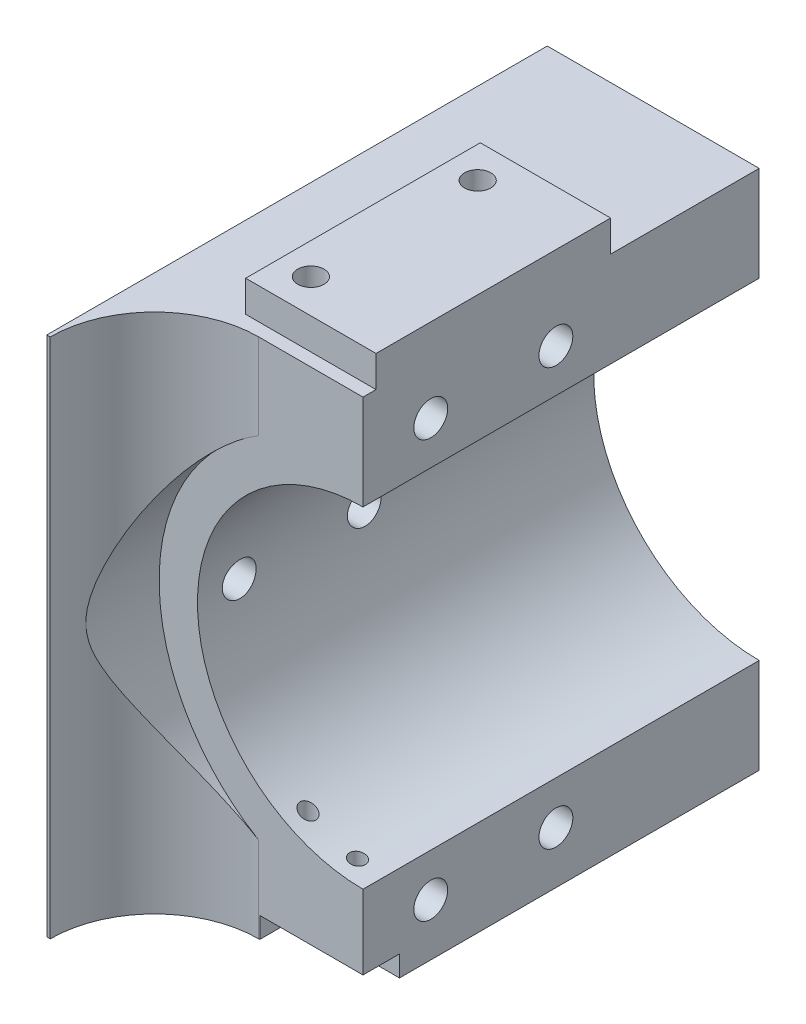
SolidWorks part; units mm, degrees
other "Markup1"
sketch "Sketch12" plane through (-50, 56, -10) normal (-0.1438, 0.9756, -0.1662) x (-0.9889, -0.1353, 0.0611)
material "6061-T6 (SS)"
ref_plane "Front Plane" through (0, 0, 0) normal (0, 0, 1) x (1, 0, 0)
ref_plane "Top Plane" through (0, 0, 0) normal (0, 1, 0) x (1, 0, 0)
ref_plane "Right Plane" through (0, 0, 0) normal (1, 0, 0) x (0, 0, -1)
sketch "Sketch1" plane through (0, 0, 0) normal (0, 0, 1) x (1, 0, 0)
  circle A2 centre (0, 0) radius 31.75
  circle A4 centre (0, 0) radius 39.1
  circle A5 centre (0, 0) radius 38.1 construction
  dimension "D1" = 1
  dimension "D2" = 63.5
extrude "Centre Hole for L2" add sketch "Sketch1" along normal blind 40 and the other way blind 10 contours A4 | A2
sketch "Sketch2" plane through (0, 0, 40) normal (0, 0, 1) x (1, 0, 0)
  line L0 (0, 48.4974) -> (0, 0) construction
  line L5 (-50, 50) -> (-50, -50)
  line L12 (0, 0) -> (72.986, 0) construction
  line L16 (-50, 50) -> (50, 50)
  line L17 (50, 50) -> (50, -50)
  line L18 (-50, -50) -> (50, -50)
  circle A2 centre (0, 0) radius 39.1
  circle A3 centre (0, 0) radius 39.1 construction
  point P13 (0, 50)
  dimension "D1" = 50
  dimension "D2" = 100
extrude "Main Structure" add sketch "Sketch2" along normal blind 60 and the other way blind 50 contours L5 L18 L17 L16 A2
sketch "Sketch3" plane through (-50, 0, 0) normal (-1, 0, 0) x (0, 0, 1)
  line L0 (100, 50) -> (100, -50) construction
  line L1 (100, 50) -> (100, -50)
  line L2 (-10, 50) -> (100, 50) construction
  line L3 (-10, -50) -> (100, -50) construction
  line L4 (-10, 50) -> (100, 50) construction
  arc A0 (100, 50) -> (100, -50) centre (100, 0) cw
extrude "Bearing Curve" add sketch "Sketch3" against normal blind 10 contours A0 L1
mirror "Upright Mirror" about plane through (0, 0, 0) normal (1, 0, 0) of "Bearing Curve"
sketch "Sketch6" plane through (-50, 0, 0) normal (-1, 0, 0) x (0, 0, 1)
  circle A0 centre (100, 0) radius 10.5
  dimension "D1" = 21
extrude "Shaft Hole" cut sketch "Sketch6" against normal up to surface (10 mm away) up to face at (-40, 0, 125)
sketch "Sketch4" plane through (0, 50, 0) normal (0, 1, 0) x (1, 0, 0)
  line L0 (0, -100) -> (0, 10) construction
  line L3 (-40, -100) -> (-40, -60)
  line L6 (40, -100) -> (40, -60)
  line L7 (-50, 10) -> (50, 10) construction
  line L8 (-40, -100) -> (40, -100) construction
  line L9 (-20, -40) -> (20, -40)
  line L10 (-40, -100) -> (40, -100)
  arc A0 (-40, -60) -> (-20, -40) centre (-20, -60) cw
  arc A1 (40, -60) -> (20, -40) centre (20, -60) ccw
  point P17 (0, -100)
  dimension "D2" = 20
  dimension "D1" = 50
extrude "Wrist Cutout" cut sketch "Sketch4" against normal through all
ref_plane "Plane1" through (0, 0, 0) normal (-1, 0, 0) x (0, 0, 1)
other "SurfaceCut1"
sketch "Sketch11" plane through (0, 50, 0) normal (0, 1, 0) x (1, 0, 0)
  line L0 (0, -40) -> (0, 10) construction
  line L1 (0, -37.5) -> (-25, -37.5)
  line L2 (0, -37.5) -> (0, 7.5)
  line L3 (0, 7.5) -> (-25, 7.5)
  line L4 (-25, -37.5) -> (-25, 7.5)
  line L5 (-50, 10) -> (0, 10) construction
  circle A0 centre (-19, 1) radius 2.525
  circle A1 centre (-19, -31) radius 2.525
  dimension "D4" = 5.05
  dimension "D5" = 19
  dimension "D6" = 6.5
  dimension "D7" = 5.05
  dimension "D8" = 19
  dimension "D1" = 45
  dimension "D2" = 25
  dimension "D3" = 2.5
  dimension "6.5" = 6.5
extrude "Boss-Extrude1" add sketch "Sketch11" along normal blind 6
sketch "Sketch15" plane through (0, -50, 0) normal (0, -1, 0) x (-1, 0, 0)
  line L1 (0, -40) -> (19.8, -40)
  line L2 (0, -40) -> (0, -33)
  line L3 (0, -33) -> (19.8, -33)
  line L4 (19.8, -40) -> (19.8, -33)
  dimension "D1" = 19.8
  dimension "D2" = 7
extrude "Cut-Extrude4" cut sketch "Sketch15" against normal blind 4
sketch "Sketch16" plane through (0, -46, 0) normal (0, -1, 0) x (-1, 0, 0)
  line L0 (19.8, -40) -> (19.8, -33) construction
  line L1 (19.8, -33) -> (0, -33) construction
  line L2 (14.65, -35.9) -> (4.8172, -35.9) construction
  circle A0 centre (14.65, -35.9) radius 1.5
  circle A1 centre (5.15, -35.9) radius 1.5
  point P4 (19.8, -36.5)
  dimension "D1" = 3
  dimension "D2" = 5.15
  dimension "D3" = 2.9
  dimension "D4" = 3
  dimension "D5" = 9.5
extrude "Cut-Extrude5" cut sketch "Sketch16" against normal up to surface (17.8319 mm away)
sketch "Sketch18" plane through (-50, 0, 0) normal (-1, 0, 0) x (0, 0, 1)
  line L2 (-10, 50) -> (-10, -50) construction
  line L4 (-10, 50) -> (100, 50) construction
  circle A0 centre (8, 0) radius 3.25
  circle A1 centre (32, 0) radius 3.25
  dimension "D1" = 6.5
  dimension "D2" = 6.5
  dimension "D3" = 18
  dimension "D4" = 50
  dimension "D6" = 24
extrude "Cut-Extrude6" cut sketch "Sketch18" against normal through all and the other way through all
sketch "Sketch19" plane through (-40, 0, 0) normal (1, 0, 0) x (0, 0, -1)
  line L3 (-60, 50) -> (-100, 50)
  line L4 (-100, -50) -> (-60, -50)
  line L5 (-60, -50) -> (-60, 50)
  line L6 (-60, 50) -> (-100, 50)
  line L7 (-100, -50) -> (-60, -50)
  line L8 (-60, -50) -> (-60, 50)
  arc A1 (-100, 50) -> (-100, -50) centre (-100, 0) ccw
  arc A2 (-100, 50) -> (-100, -50) centre (-100, 0) ccw
  dimension "D1" = 0
extrude "Cut-Extrude7" cut sketch "Sketch19" against normal blind 1.5875
sketch "Sketch9" plane through (-41.5875, 0, 0) normal (1, 0, 0) x (0, 0, -1)
  circle A0 centre (-100, 0) radius 12.05
  dimension "D1" = 24.1
extrude "Bearing" cut sketch "Sketch9" against normal blind 5
sketch "Sketch20" plane through (-50, 0, 0) normal (-1, 0, 0) x (0, 0, 1)
  line L3 (-10, -50) -> (100, -50)
  line L4 (100, 50) -> (-10, 50)
  line L5 (-10, 50) -> (-10, -50)
  line L6 (-10, -50) -> (100, -50)
  line L7 (100, 50) -> (-10, 50)
  line L8 (-10, 50) -> (-10, -50)
  arc A1 (100, -50) -> (100, 50) centre (100, 0) ccw
  arc A2 (100, -50) -> (100, 50) centre (100, 0) ccw
  dimension "D1" = 0
extrude "Cut-Extrude8" cut sketch "Sketch20" against normal blind 3
sketch "Sketch21" plane through (-47, 0, 0) normal (-1, 0, 0) x (0, 0, 1)
  line L0 (3, -40) -> (27, -40) construction
  line L1 (8, 0) -> (8, -40) construction
  line L2 (100, 0) -> (-10, 0) construction
  line L3 (-10, 50) -> (-10, -50) construction
  line L4 (100, 0) -> (150, 0) construction
  circle A2 centre (3, -40) radius 3.25
  circle A3 centre (27, -40) radius 3.25
  circle A4 centre (27, 40) radius 3.25
  circle A5 centre (3, 40) radius 3.25
  arc A6 (100, -50) -> (100, 50) centre (100, 0) ccw construction
  circle A7 centre (125, 0) radius 1.65
  circle A8 centre (32, 0) radius 3.25 construction
  dimension "D1" = 6.5
  dimension "D5" = 3.3
  dimension "D2" = 40
  dimension "D3" = 5
  dimension "D4" = 5
extrude "Cut-Extrude9" cut sketch "Sketch21" against normal through all
sketch "Sketch22" plane through (-47, 0, 0) normal (-1, 0, 0) x (0, 0, 1)
  line L3 (-10, 50) -> (-10, -50)
  line L4 (-10, -50) -> (100, -50)
  line L5 (100, 50) -> (-10, 50)
  line L6 (-10, 50) -> (-10, -50)
  line L7 (-10, -50) -> (100, -50)
  line L8 (100, 50) -> (-10, 50)
  arc A1 (100, -50) -> (100, 50) centre (100, 0) ccw
  arc A2 (100, -50) -> (100, 50) centre (100, 0) ccw
  dimension "D1" = 0
extrude "Cut-Extrude10" cut sketch "Sketch22" against normal blind 6.35
sketch "Sketch23" plane through (0, -50, 0) normal (0, -1, 0) x (-1, 0, 0)
  line L0 (0, -33) -> (0, 10) construction
  line L1 (40.65, 0.25) -> (0, 0.25) construction
  circle A0 centre (15, 3.25) radius 2.275
  dimension "D1" = 4.55
  dimension "D2" = 15
  dimension "D3" = 3
extrude "Cut-Extrude11" cut sketch "Sketch23" against normal blind 6
chamfer "Chamfer1" distance 0.5 angle 45 1 edges at (-15, -50, -5.525)
sketch "Sketch24" plane through (0, 0, -10) normal (0, 0, -1) x (-1, 0, 0)
  line L5 (40.65, -50) -> (40.65, 50)
  line L6 (40.65, 50) -> (0, 50)
  line L7 (0, 50) -> (0, 31.75)
  line L8 (0, -31.75) -> (0, -50)
  line L9 (0, -50) -> (40.65, -50)
  line L10 (40.65, -50) -> (40.65, 50)
  line L11 (40.65, 50) -> (0, 50)
  line L12 (0, 50) -> (0, 31.75)
  line L13 (0, -31.75) -> (0, -50)
  line L14 (0, -50) -> (40.65, -50)
  arc A1 (0, -31.75) -> (0, 31.75) centre (0, 0) ccw
  arc A2 (0, -31.75) -> (0, 31.75) centre (0, 0) ccw
  dimension "D1" = 0
extrude "Boss-Extrude2" add sketch "Sketch24" along normal blind 26
